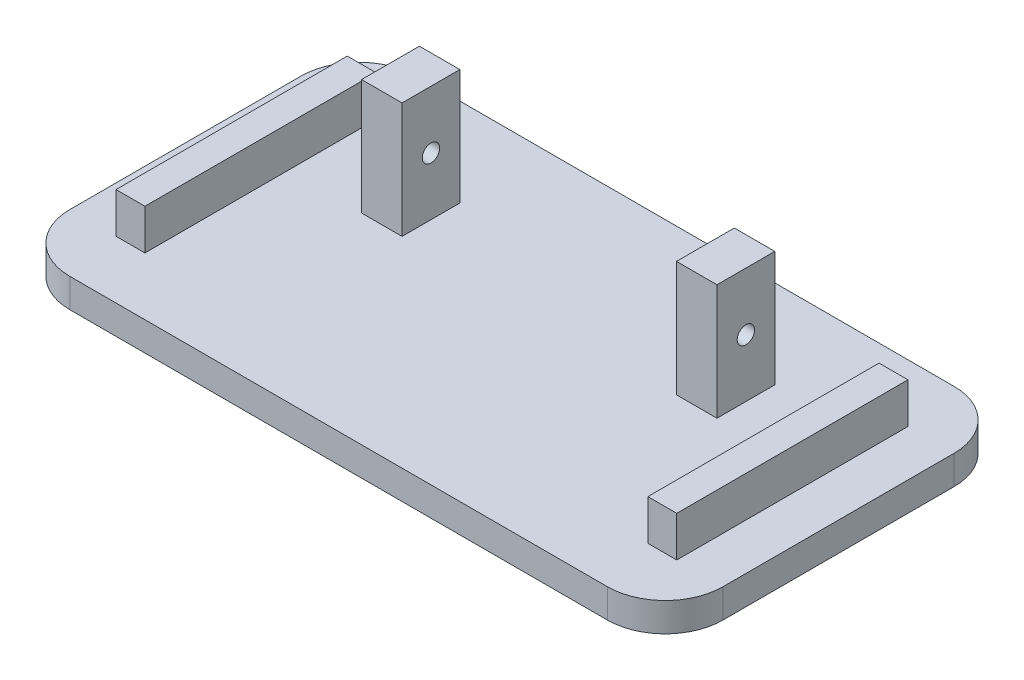
SolidWorks part; units mm, degrees
material "ABS"
ref_plane "Plano frontal" through (0, 0, 0) normal (0, 0, 1) x (1, 0, 0)
ref_plane "Plano superior" through (0, 0, 0) normal (0, 1, 0) x (1, 0, 0)
ref_plane "Plano direito" through (0, 0, 0) normal (1, 0, 0) x (0, 0, -1)
sketch "Esboço1" plane through (0, 0, 0) normal (0, 1, 0) x (1, 0, 0)
  line L1 (-13.2145, 15.5332) -> (79.7855, 15.5332)
  line L2 (-23.2145, 5.5332) -> (-23.2145, -34.4668)
  line L3 (-13.2145, -44.4668) -> (79.7855, -44.4668)
  line L4 (89.7855, 5.5332) -> (89.7855, -34.4668)
  arc A0 (89.7855, 5.5332) -> (79.7855, 15.5332) centre (79.7855, 5.5332) ccw
  arc A1 (89.7855, -34.4668) -> (79.7855, -44.4668) centre (79.7855, -34.4668) cw
  arc A2 (-13.2145, -44.4668) -> (-23.2145, -34.4668) centre (-13.2145, -34.4668) cw
  arc A3 (-23.2145, 5.5332) -> (-13.2145, 15.5332) centre (-13.2145, 5.5332) cw
  point P4 (33.2855, 15.5332)
  point P7 (89.7855, 15.5332)
  point P12 (-23.2145, -44.4668)
  point P15 (-23.2145, 15.5332)
  dimension "D4" = 10
  dimension "D1" = 113
  dimension "D2" = 56.5
  dimension "D3" = 60
extrude "Ressalto-extrusão1" add sketch "Esboço1" along normal blind 5
sketch "Esboço2" plane through (0, 5, 0) normal (0, 1, 0) x (1, 0, 0)
  line L1 (-7.4545, -9.7476) -> (-7.4545, 0.2524) construction
  line L2 (65.1855, -9.7476) -> (65.1855, 0.2524) construction
  line L3 (-7.4545, -9.7476) -> (65.1855, -9.7476) construction
  line L4 (-7.4545, 0.2524) -> (65.1855, 0.2524) construction
  line L5 (57.0255, 0.2524) -> (57.0255, -9.7476)
  line L6 (2.5455, 0.2524) -> (9.5455, 0.2524)
  line L7 (2.5455, -9.7476) -> (9.5455, -9.7476)
  line L8 (2.5455, 0.2524) -> (2.5455, -9.7476)
  line L9 (9.5455, 0.2524) -> (9.5455, -9.7476)
  line L10 (64.0255, 0.2524) -> (64.0255, -9.7476)
  line L11 (57.0255, 0.2524) -> (64.0255, 0.2524)
  line L12 (57.0255, -9.7476) -> (64.0255, -9.7476)
  line L13 (89.7855, -34.4668) -> (89.7855, 5.5332) construction
  line L15 (-23.2145, 5.5332) -> (-23.2145, -34.4668) construction
  point P8 (2.5455, -4.7476)
  dimension "D1" = 47.48
  dimension "D2" = 7
  dimension "D3" = 25.76
  dimension "D4" = 25.76
  dimension "D5" = 7
extrude "Ressalto-extrusão2" add sketch "Esboço2" along normal blind 20
sketch "Esboço4" plane through (2.5455, 0, 0) normal (-1, 0, 0) x (0, 0, 1)
  line L0 (-0.2524, 5) -> (9.7476, 5) construction
  line L1 (9.7476, 25) -> (9.7476, 5) construction
  circle A0 centre (4.7476, 15) radius 1.5
  dimension "D1" = 10
  dimension "D2" = 5
extrude "Corte-extrusão1" cut sketch "Esboço4" against normal through all
sketch "Esboço5" plane through (0, 5, 0) normal (0, 1, 0) x (1, 0, 0)
  line L0 (79.7855, 15.5332) -> (-13.2145, 15.5332) construction
  line L1 (-15.2145, 5.5332) -> (-10.2145, 5.5332)
  line L2 (-15.2145, 5.5332) -> (-15.2145, -34.4668)
  line L3 (-15.2145, -34.4668) -> (-10.2145, -34.4668)
  line L4 (-10.2145, 5.5332) -> (-10.2145, -34.4668)
  line L5 (-13.2145, -44.4668) -> (79.7855, -44.4668) construction
  line L6 (-23.2145, 5.5332) -> (-23.2145, -34.4668) construction
  line L7 (89.7855, -34.4668) -> (89.7855, 5.5332) construction
  line L8 (76.7855, 5.5332) -> (81.7855, 5.5332)
  line L9 (76.7855, 5.5332) -> (76.7855, -34.4668)
  line L10 (76.7855, -34.4668) -> (81.7855, -34.4668)
  line L11 (81.7855, 5.5332) -> (81.7855, -34.4668)
  dimension "D1" = 10
  dimension "D2" = 10
  dimension "D3" = 8
  dimension "D4" = 40
  dimension "D5" = 10
  dimension "D6" = 8
extrude "Ressalto-extrusão3" add sketch "Esboço5" along normal blind 7
